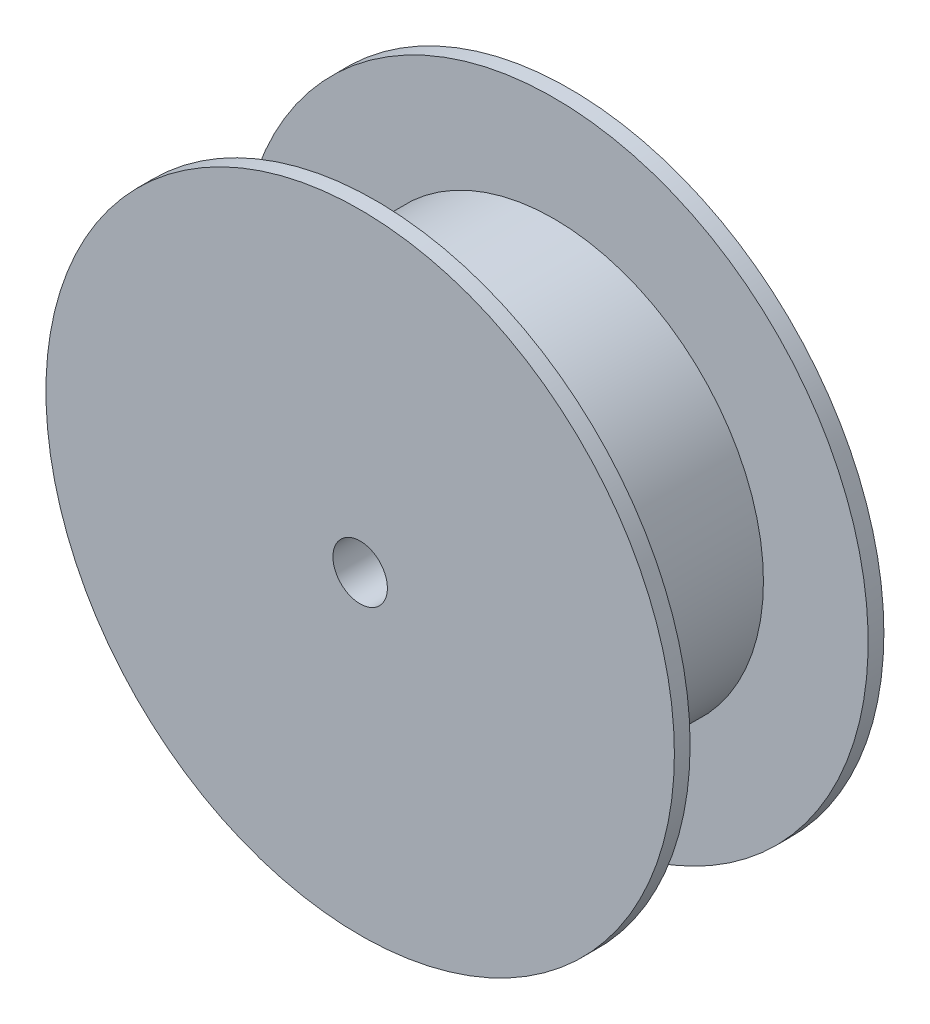
SolidWorks part; units mm, degrees
material "Custom Plastic"
ref_plane "Front Plane" through (0, 0, 0) normal (0, 0, 1) x (1, 0, 0)
ref_plane "Top Plane" through (0, 0, 0) normal (0, 1, 0) x (1, 0, 0)
ref_plane "Right Plane" through (0, 0, 0) normal (1, 0, 0) x (0, 0, -1)
sketch "Sketch1" plane through (0, 0, 0) normal (0, 0, 1) x (1, 0, 0)
  circle A0 centre (0, 0) radius 30
  circle A1 centre (0, 0) radius 20
  dimension "D1" = 60
  dimension "D2" = 40
extrude "Boss-Extrude1" add sketch "Sketch1" along normal mid plane 20 contours A1 | A0 A1
ref_plane "Plane1" through (0, 0, 5) normal (0, 0, 1) x (1, 0, 0)
sketch "Sketch2" plane through (0, 0, 5) normal (0, 0, 1) x (1, 0, 0)
  circle A0 centre (0, 0) radius 20
  dimension "D1" = 40
extrude "Cut-Extrude1" cut sketch "Sketch2" against normal mid plane 7 flip side to cut
mirror "Mirror1" about plane through (0, 0, 0) normal (0, 0, 1) of "Cut-Extrude1"
sketch "Sketch4" plane through (0, 0, -10) normal (0, 0, -1) x (-1, 0, 0)
  line L1 (0, 0) -> (0, -2.6) construction
  circle A0 centre (0, 0) radius 2.6
  point P1 (-1.5874, 2.0591)
  dimension "D1" = 5.2
extrude "Cut-Extrude3" cut sketch "Sketch4" against normal through all both
sketch "Sketch5" plane through (0, 0, 1.5) normal (0, 0, 1) x (1, 0, 0)
  circle A0 centre (0, 0) radius 20 construction
  circle A1 centre (0, 0) radius 30
  circle A2 centre (0, 0) radius 30
  circle A3 centre (0, 0) radius 20
  dimension "D1" = 0
extrude "Cut-Extrude4" cut sketch "Sketch5" against normal up to surface (3 mm away) up to face at (20, 0, -1.5)
